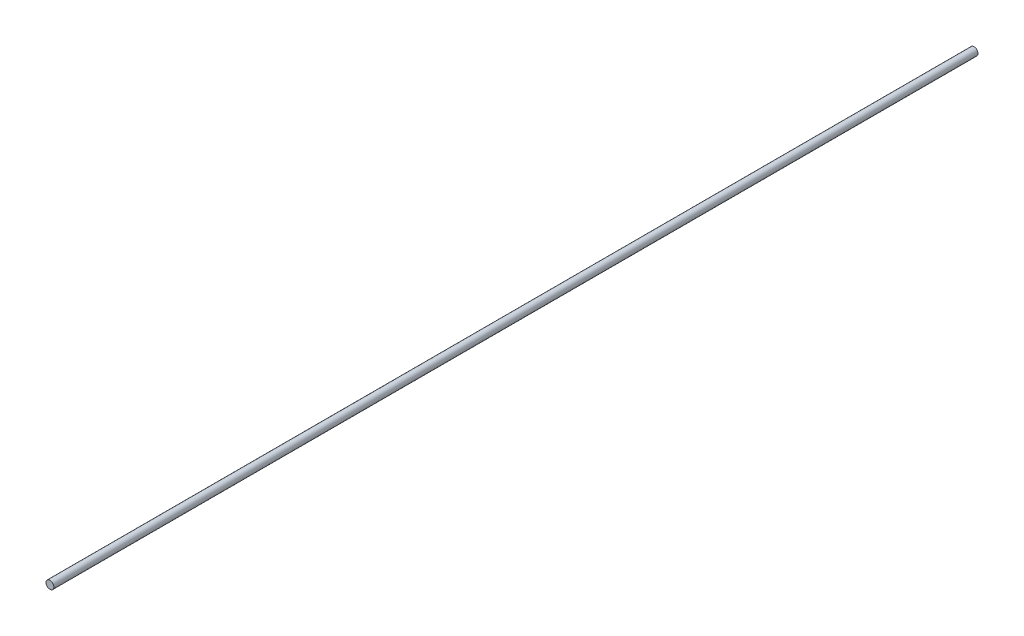
SolidWorks part; units mm, degrees
material "FEA Aluminum"
ref_plane "Front Plane" through (0, 0, 0) normal (0, 0, 1) x (1, 0, 0)
ref_plane "Top Plane" through (0, 0, 0) normal (0, 1, 0) x (1, 0, 0)
ref_plane "Right Plane" through (0, 0, 0) normal (1, 0, 0) x (0, 0, -1)
sketch "Sketch1" plane through (0, 0, 0) normal (0, 0, 1) x (1, 0, 0)
  circle A0 centre (0, 0) radius 8.89
  dimension "D1" = 17.78
extrude "Boss-Extrude1" add sketch "Sketch1" along normal blind 2094.6569
equation "\"d\"= 0.70"
equation "\"A\"= pi * \"d\" ^ 2 / 4"
equation "\"F\" = 420"
equation "\"E\"= 10e6"
equation "\"def\"= 0.009"
equation "\"L\"= \"def\" * \"A\" * \"E\" / \"F\""
equation "\"D1@Sketch1\"=\"d\""
equation "\"D1@Boss-Extrude1\"=\"L\""
